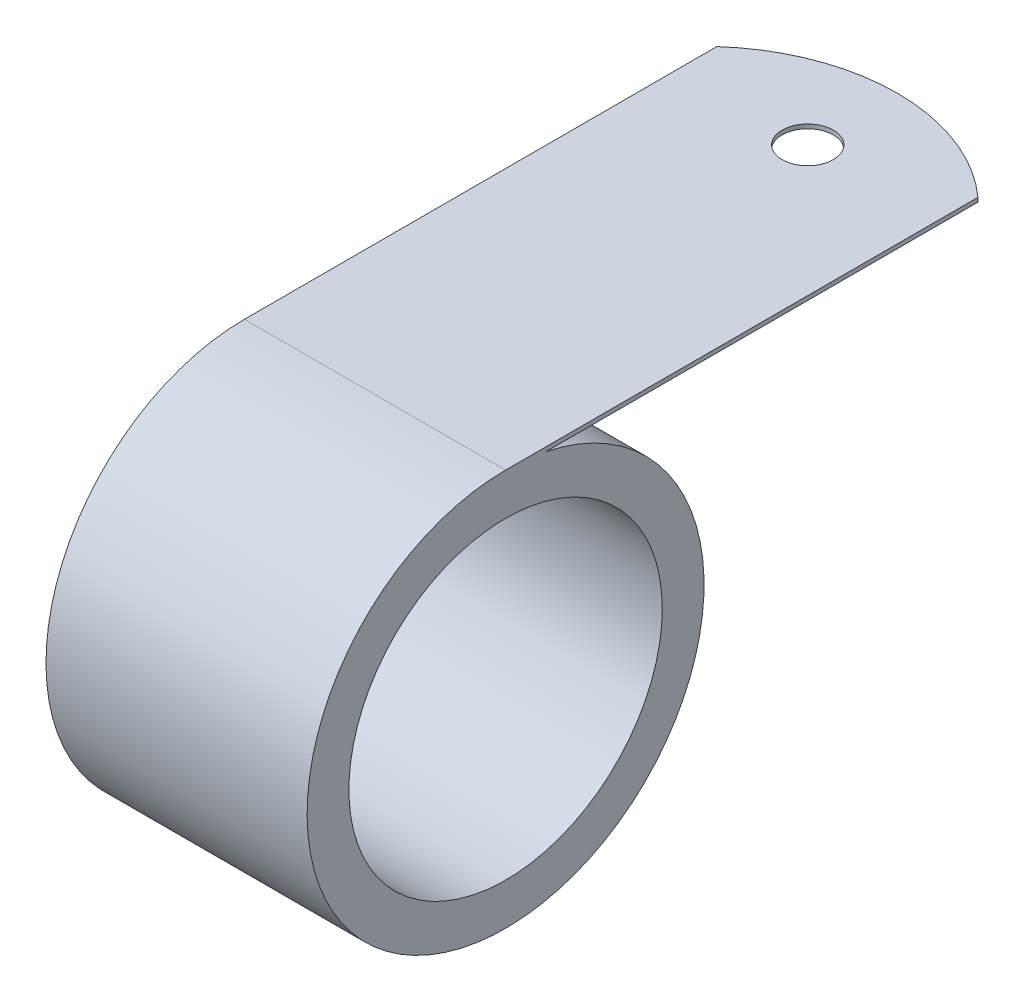
SolidWorks part; units mm, degrees
ref_plane "Front" through (0, 0, 0) normal (0, 0, 1) x (1, 0, 0)
ref_plane "Top" through (0, 0, 0) normal (0, 1, 0) x (1, 0, 0)
ref_plane "Right" through (0, 0, 0) normal (1, 0, 0) x (0, 0, -1)
sketch "Sketch1" plane through (0, 0, 0) normal (1, 0, 0) x (0, 0, -1)
  line L0 (0, 19.304) -> (50.8, 19.304)
  line L1 (3.9402, 18.8976) -> (50.8, 18.8976)
  line L2 (50.8, 18.8976) -> (50.8, 19.304)
  line L3 (0, 19.304) -> (0, -19.304) construction
  circle A0 centre (0, 0) radius 15.24
  arc A1 (0, 19.304) -> (3.9402, 18.8976) centre (0, 0) ccw
  dimension "D2" = 50.8
extrude "Boss-Extrude1" add sketch "Sketch1" along normal mid plane 25.4
sketch "Sketch2" plane through (0, 19.304, 0) normal (0, 1, 0) x (1, 0, 0)
  line L0 (0, 31.75) -> (0, 50.8) construction
  line L1 (12.7, 50.8) -> (-12.7, 50.8) construction
  line L2 (-12.7, 45.949) -> (-12.7, 51.435)
  line L3 (-12.7, 50.8) -> (-12.7, 0) construction
  line L4 (-12.7, 51.435) -> (12.7, 51.435)
  line L5 (12.7, 45.949) -> (12.7, 51.435)
  line L6 (12.7, 50.8) -> (12.7, 0) construction
  arc A0 (12.7, 45.949) -> (-12.7, 45.949) centre (0, 31.75) ccw
  circle A1 centre (0, 42.0878) radius 2.4892
  dimension "D2" = 0.635
extrude "OneHole" cut sketch "Sketch2" against normal up to next
sketch "Sketch4" plane through (0, 19.304, 0) normal (0, 1, 0) x (1, 0, 0)
  line L0 (0, 50.8) -> (0, 42.0878) construction
  line L2 (9.525, 42.0878) -> (-9.525, 42.0878) construction
  circle A0 centre (-9.525, 42.0878) radius 2.4892
  circle A1 centre (9.525, 42.0878) radius 2.4892
  dimension "D1" = 4.9784
  dimension "D2" = 8.7122
  dimension "D3" = 19.05
extrude "TwoHole" [suppressed] cut sketch "Sketch4" against normal up to next
equation "\"D2@Sketch1\" = \"Width@Boss-Extrude1\"*2"
equation "\"D1@Sketch4\" = \"HoleDia@Sketch2\""
equation "\"D2@Sketch4\" = \"HolePosition@Sketch2\""
